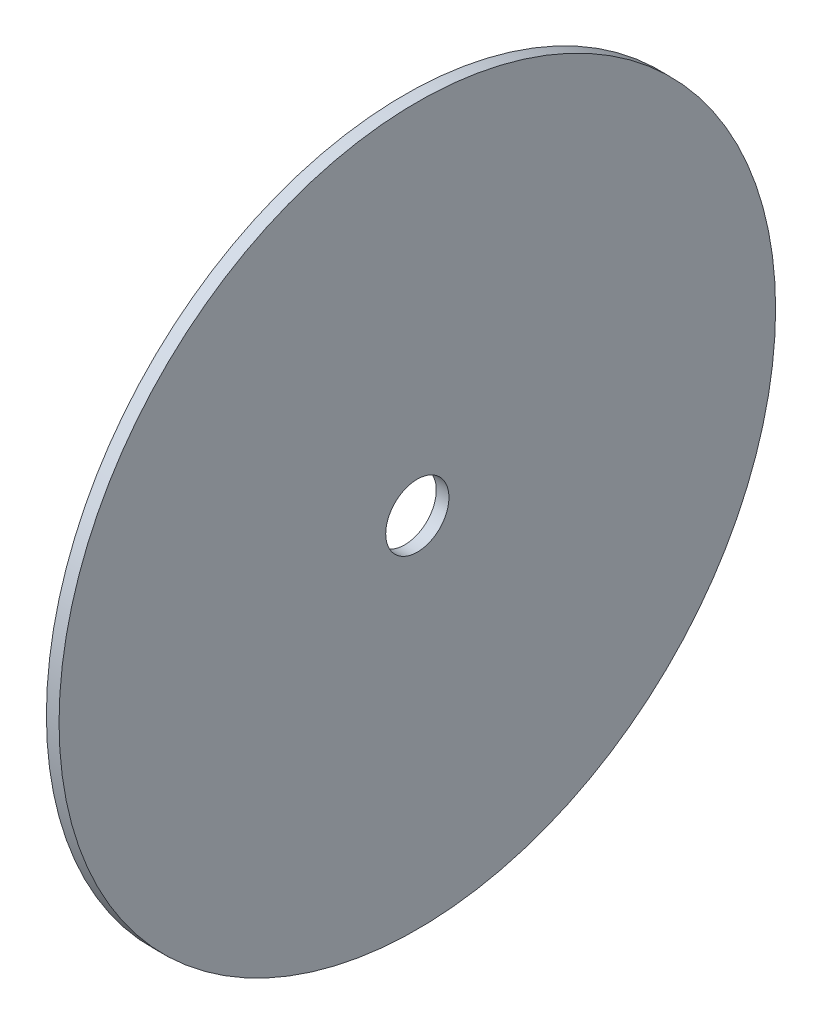
SolidWorks part; units mm, degrees
ref_plane "前视基准面" through (0, 0, 0) normal (0, 0, 1) x (1, 0, 0)
ref_plane "上视基准面" through (0, 0, 0) normal (0, 1, 0) x (1, 0, 0)
ref_plane "右视基准面" through (0, 0, 0) normal (1, 0, 0) x (0, 0, -1)
sketch "草图1" plane through (0, 0, 0) normal (0, 0, 1) x (1, 0, 0)
  line L0 (-23.9151, 0) -> (21.7075, 0) construction
  line L1 (0, 19.7264) -> (0, -20.0094) construction
  line L2 (0, 1.5) -> (0, 17)
  line L3 (0, 17) -> (-0.6, 17)
  line L4 (-0.6, 17) -> (-0.6, 1.5)
  line L5 (-0.6, 1.5) -> (0, 1.5)
  dimension "D1" = 3
  dimension "D2" = 34
  dimension "D3" = 0.6
revolve "旋转1" add sketch "草图1" angle 360 about L0
